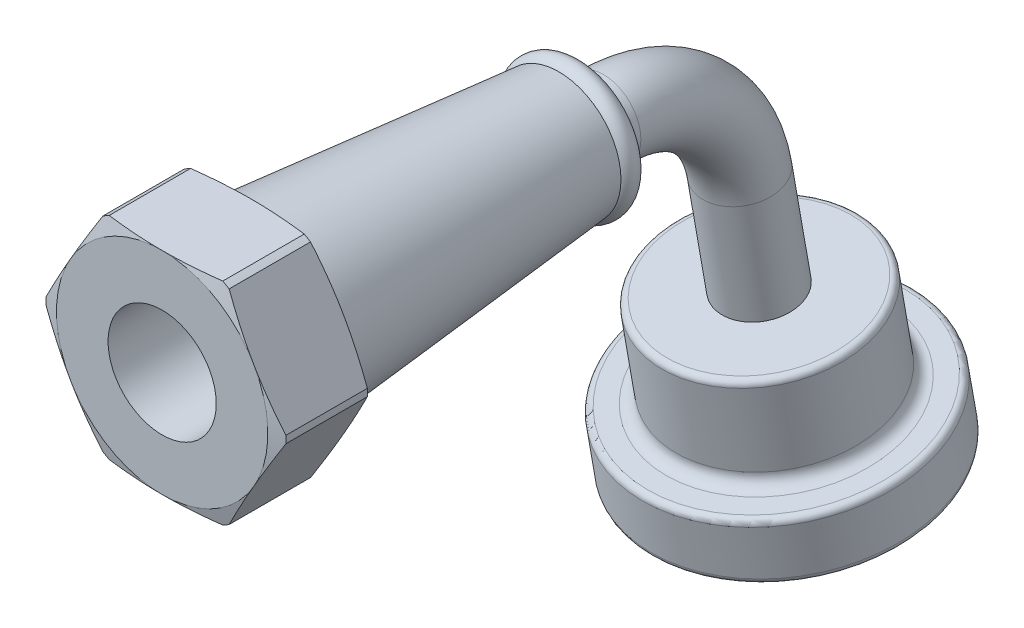
SolidWorks part; units mm, degrees
material "Plain Carbon Steel"
ref_plane "Front Plane" through (0, 0, 0) normal (0, 0, 1) x (1, 0, 0)
ref_plane "Top Plane" through (0, 0, 0) normal (0, 1, 0) x (1, 0, 0)
ref_plane "Right Plane" through (0, 0, 0) normal (1, 0, 0) x (0, 0, -1)
sketch "Sketch1" plane through (0, 0, 0) normal (1, 0, 0) x (0, 0, -1)
  line L0 (0, 0) -> (59.2715, 0) construction
  line L1 (0, 4.35) -> (0, 8.5)
  line L3 (7.5, 18.2528) -> (7.5, 7.25) construction
  line L4 (7.5, 7.25) -> (31.9, 5)
  line L5 (33.5, 1.8) -> (13, 1.8)
  line L6 (33.5, 5) -> (33.5, 1.8)
  line L7 (13, 1.8) -> (13, 4.35)
  line L8 (13, 4.35) -> (0, 4.35)
  line L9 (7.5, 7.25) -> (6.8569, 9.65)
  line L10 (6.8569, 9.65) -> (0.3081, 9.65)
  line L11 (0.3081, 9.65) -> (0, 8.5)
  arc A0 (31.9, 5) -> (33.5, 5) centre (32.7, 4.4) cw
  dimension "D12" = 1
  dimension "D1" = 8.7
  dimension "D2" = 13
  dimension "D3" = 3.6
  dimension "D4" = 33.5
  dimension "D5" = 10
  dimension "D6" = 14.5
  dimension "D7" = 19.3
  dimension "D8" = 15
  dimension "D9" = 15
  dimension "D10" = 7.5
  dimension "D11" = 1.6
  dimension "D13" = 17
revolve "Revolve1" add sketch "Sketch1" angle 360 about L0
cosmetic thread "Cosmetic Thread1" parameters "D2"=10
sketch "Sketch2" plane through (0, 0, 0) normal (0, 0, 1) x (1, 0, 0)
  line L1 (9.815, 0) -> (4.9075, 8.5)
  line L2 (4.9075, 8.5) -> (-4.9075, 8.5)
  line L3 (-4.9075, 8.5) -> (-9.815, 0)
  line L4 (-9.815, 0) -> (-4.9075, -8.5)
  line L5 (-4.9075, -8.5) -> (4.9075, -8.5)
  line L6 (4.9075, -8.5) -> (9.815, 0)
  circle A0 centre (0, 0) radius 8.5 construction
  dimension "D1" = 17
extrude "Cut-Extrude1" cut sketch "Sketch2" against normal blind 10 flip side to cut
sketch "Sketch3" plane through (0, 0, 0) normal (1, 0, 0) x (0, 0, -1)
  line L0 (33.5, 0) -> (35.5, 0)
  line L1 (33.5, -1.8) -> (33.5, 1.8) construction
  line L2 (33.5, -5) -> (33.5, 5) construction
  line L3 (46.4456, -9.1844) -> (48, -18)
  arc A0 (35.5, 0) -> (46.4456, -9.1844) centre (35.5, -11.1144) cw
  dimension "D2" = 100
  dimension "D1" = 2
  dimension "D3" = 18
  dimension "D4" = 48
sketch "Sketch4" plane through (0, 0, -33.5) normal (0, 0, -1) x (-1, 0, 0)
  circle A0 centre (0, 0) radius 3
  circle A1 centre (0, 0) radius 1.8
  circle A2 centre (0, 0) radius 1.8 construction
  dimension "D1" = 6
sweep "Sweep1" add profiles "Sketch4" path "Sketch3"
sketch "Sketch5" plane through (0, 0, 0) normal (1, 0, 0) x (0, 0, -1)
  line L0 (48, -18) -> (52.8033, -45.2407) construction
  line L1 (45.0456, -18.5209) -> (50.9544, -17.4791) construction
  line L2 (55.083, -29.9516) -> (61.0903, -28.8924)
  line L3 (61.0903, -28.8924) -> (60.2221, -23.9683)
  line L4 (60.2221, -23.9683) -> (57.2676, -24.4893)
  line L5 (57.2676, -24.4893) -> (55.8785, -16.6108)
  line L6 (55.8785, -16.6108) -> (49.7727, -17.6874)
  line L7 (49.7727, -17.6874) -> (50.9882, -24.5811)
  line L8 (50.9882, -24.5811) -> (54.0411, -24.0428)
  line L9 (54.0411, -24.0428) -> (55.083, -29.9516)
  dimension "D1" = 16
  dimension "D2" = 13
  dimension "D3" = 5
  dimension "D4" = 3.6
  dimension "D5" = 9.8
  dimension "D6" = 6
  dimension "D7" = 22
revolve "Revolve2" add sketch "Sketch5" angle 360 about L0
fillet "Fillet1" radius 0.5 3 edges at (0, -32.7126, -39.4245) (0, -27.7886, -38.5563) (0, -19.3892, -40.1215)
fillet "Fillet2" radius 1 1 edges at (0, -27.2676, -41.5107)
